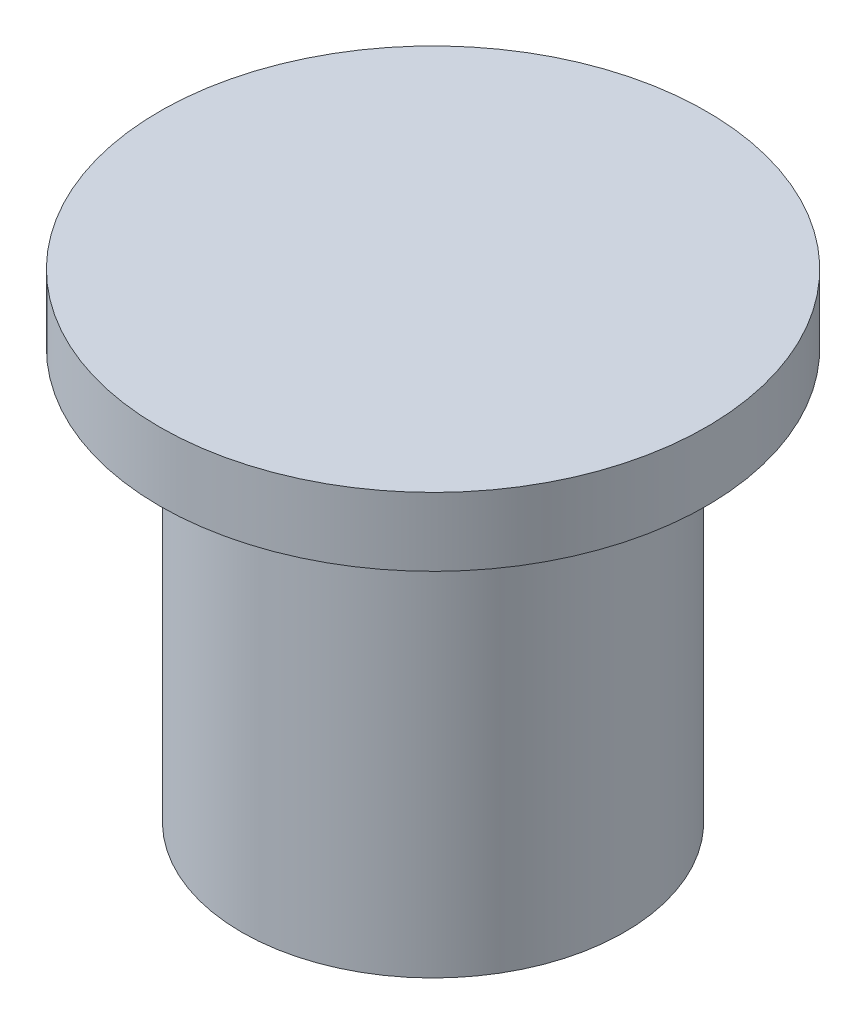
SolidWorks part; units mm, degrees
ref_plane "前视基准面" through (0, 0, 0) normal (0, 0, 1) x (1, 0, 0)
ref_plane "上视基准面" through (0, 0, 0) normal (0, 1, 0) x (1, 0, 0)
ref_plane "右视基准面" through (0, 0, 0) normal (1, 0, 0) x (0, 0, -1)
other "Configuration Table"
sketch "草图1" plane through (0, 0, 0) normal (0, 1, 0) x (1, 0, 0)
  circle A0 centre (0, 0) radius 1.4
  dimension "D1" = 2.8
extrude "凸台-拉伸1" add sketch "草图1" along normal blind 3
sketch "草图2" plane through (0, 3, 0) normal (0, 1, 0) x (1, 0, 0)
  circle A0 centre (0, 0) radius 2
  dimension "D1" = 4
extrude "凸台-拉伸2" add sketch "草图2" along normal blind 0.5
